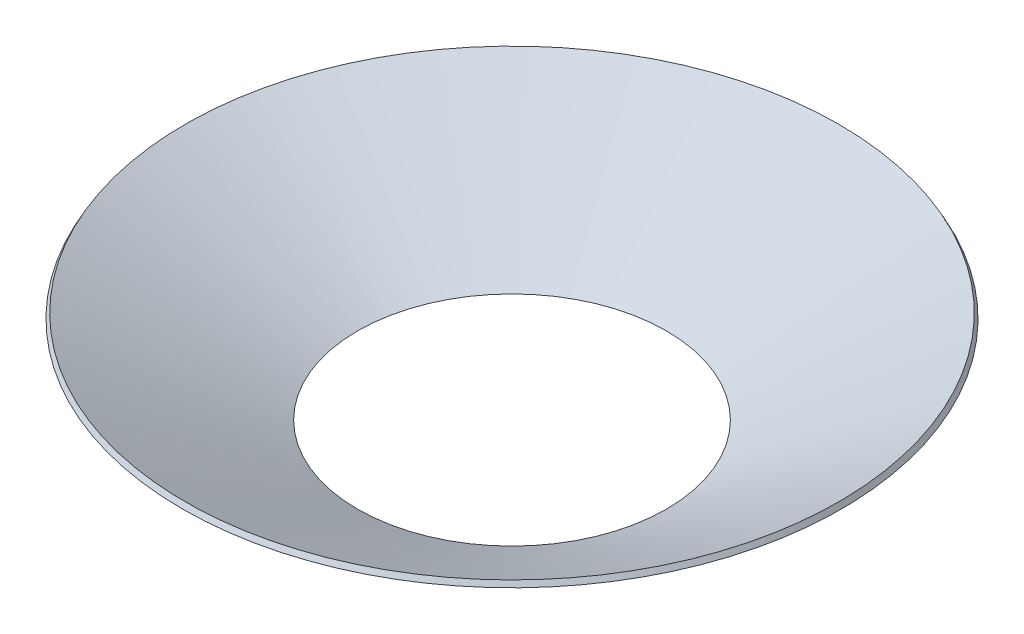
SolidWorks part; units mm, degrees
ref_plane "Front Plane" through (0, 0, 0) normal (0, 0, 1) x (1, 0, 0)
ref_plane "Top Plane" through (0, 0, 0) normal (0, 1, 0) x (1, 0, 0)
ref_plane "Right Plane" through (0, 0, 0) normal (1, 0, 0) x (0, 0, -1)
sketch "Sketch1" plane through (0, 0, 0) normal (0, 0, 1) x (1, 0, 0)
  line L0 (-29.6132, 0) -> (-58.69, 15.6191)
  line L1 (-58.69, 15.6191) -> (-58.2168, 16.5)
  line L2 (-58.2168, 16.5) -> (-27.5, 0)
  line L3 (-29.6132, 0) -> (-27.5, 0)
  line L4 (0, 0) -> (0, 38.049) construction
  line L5 (0, 0) -> (-37.9362, 0) construction
  dimension "D1" = 27.5
  dimension "D2" = 58.69
  dimension "D3" = 1
  dimension "D4" = 16.5
revolve "Revolve1" add sketch "Sketch1" angle 360 about L4
